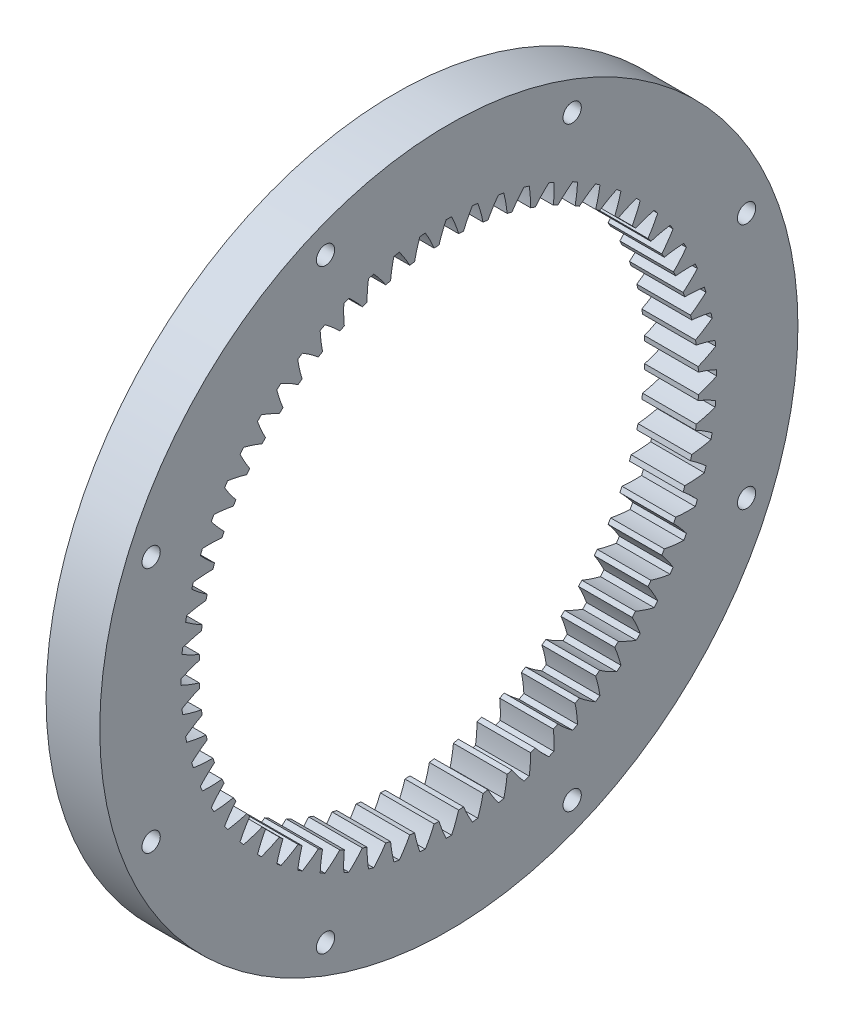
SolidWorks part; units mm, degrees
material "7075-O (SS)"
ref_plane "Plane1" through (0, 0, 0) normal (0, 0, 1) x (1, 0, 0)
ref_plane "Plane2" through (0, 0, 0) normal (0, 1, 0) x (1, 0, 0)
ref_plane "Plane3" through (0, 0, 0) normal (1, 0, 0) x (0, 0, -1)
sketch "HoldingSke" plane through (0, 0, 0) normal (0, 1, 0) x (1, 0, 0)
  line L0 (0, 0) -> (0.2922, -0.5992)
  line L1 (-15, 0) -> (100, 0) construction
  line L2 (0, 0) -> (-2.1039, 2.3779)
  line L3 (0, 0) -> (-11.863, 4.5341)
  line L4 (0, 0) -> (3.7858, 7.762)
  line L5 (0, 0) -> (-23.7986, -8.8762)
  line L6 (0, 0) -> (-10.5278, -7.1032)
  line L7 (-2.1039, 2.3779) -> (3.3635, 27.1825)
  line L8 (-76.2, 3.8779) -> (-54.61, 3.8779)
  line L9 (-71.009, 38.7566) -> (-53.1078, 45.2721)
  line L10 (-76.2, 71.12) -> (104.1128, 71.12)
  line L11 (0, 0) -> (-10, 0)
  line L12 (-76.2, 101.6) -> (-76.147, 101.6)
  line L13 (24.9733, 27.94) -> (52.9518, 28.4284)
  line L14 (24.9733, 27.94) -> (24.9743, 27.94)
  line L15 (24.9733, 27.94) -> (100.4006, 29.5858)
  circle A0 centre (0, 0) radius 55
  circle A1 centre (0, 0) radius 12.7
  circle A2 centre (0, 0) radius 12.7
  dimension "MHD" = 25.4
  dimension "Hub_dia" = 25.4
  dimension "Diameter" = 110
  dimension "Num_teeth" = 64
  dimension "Pitch" = 0.6667
  dimension "Overall_len" = 25.4
  dimension "Show_teeth" = 64
  dimension "Thickness" = 12.7
  dimension "OAL" = 25.4001
  dimension "T_dim" = 21.59
  dimension "Ap" = 20
  dimension "H" = 19.05
  dimension "Pitch_radius" = 180.3128
  dimension "Width" = 10
  dimension "Backlash" = 0.053
  dimension "Addendum_fac" = 1
  dimension "Dedendum_fac" = 1.25
  dimension "Clearance_fac" = 0.25
  dimension "Dedendum_add" = 0.001
  dimension "Module" = 1.5
sketch "BasProSke" plane through (0, 0, 0) normal (0, 1, 0) x (1, 0, 0)
  line L0 (-10, 0) -> (60, 0) construction
  line L1 (0, 46.5) -> (0, 55)
  line L2 (0, 46.5) -> (10, 46.5)
  line L3 (10, 46.5) -> (10, 55)
  line L4 (10, 55) -> (0, 55)
  dimension "Diameter" = 110
  dimension "Thickness" = 10
  dimension "Inside_diameter" = 93
revolve "Base-Revolve" add sketch "BasProSke" angle 360 about L0
sketch "TooCutSke" plane through (0, 0, 0) normal (1, 0, 0) x (0, 0, -1)
  line L3 (1.3105, 47.9821) -> (1.3105, 53.6633) construction
  line L4 (0, 0) -> (0, 59.563) construction
  line L5 (0, 0) -> (-3.3527, 68.2452) construction
  line L6 (-21.1794, 39.6032) -> (35.8053, 42.4027) construction
  circle A0 centre (0, 0) radius 48 construction
  circle A1 centre (0, 0) radius 49.876 construction
  circle A2 centre (0, 0) radius 40.5947 construction
  circle A3 centre (0, 0) radius 46.4746 construction
  arc A4 (1.8266, 46.4387) -> (0.5122, 49.8734) centre (-21.1794, 39.6032) ccw
  arc A5 (1.8266, 46.4387) -> (-1.8266, 46.4387) centre (0, 0) ccw
  arc A6 (0.5122, 49.8734) -> (-0.5122, 49.8734) centre (0, 0) ccw
  arc A7 (-0.5122, 49.8734) -> (-1.8266, 46.4387) centre (21.1794, 39.6032) ccw
  dimension "Pitch_dia" = 96
  dimension "Base_dia" = 81.1894
  dimension "Root_dia" = 99.752
  dimension "Overcut_dia" = 92.9492
  dimension "Flank_rad" = 24
  dimension "Half_ang" = 2.813
  dimension "Half_CT" = 1.3105
extrude "ToothCut" cut sketch "TooCutSke" along normal through all
fillet "Breaks" [suppressed] radius 0.15
fillet "RootFillets" [suppressed] radius 0.376
pattern_circular "TeethCuts" count 64 over 360 about axis through (0, 0, 0) along (1, 0, 0) of "RootFillets", "Breaks", "ToothCut"
sketch "Croquis1" plane through (10, 0, 0) normal (1, 0, 0) x (0, 0, -1)
  circle A0 centre (0, 0) radius 65
  circle A1 centre (0, 0) radius 55 construction
  circle A2 centre (0, 0) radius 55
  dimension "DiametroExterior" = 130
extrude "Saliente-Extruir1" add sketch "Croquis1" against normal up to surface (10 mm away) up to face at (0, 0, 55)
hole_wizard "Taladro de margen para M31" positions "Croquis2" profile "Croquis3" hole size "M3" standard "Ansi Metric"
sketch "Croquis2" plane through (10, 0, 0) normal (1, 0, 0) x (0, 0, -1)
  line L0 (0, 0) -> (22.961, 55.4328) construction
  line L3 (0, 0) -> (-22.961, -55.4328) construction
  point P0 (22.961, 55.4328)
  point P13 (55.4328, 22.961)
  point P14 (55.4328, -22.961)
  point P15 (22.961, -55.4328)
  point P16 (-22.961, -55.4328)
  point P17 (-55.4328, -22.961)
  point P18 (-55.4328, 22.961)
  point P19 (-22.961, 55.4328)
  dimension "RadioTaladro" = 60
  dimension "D2" = 22.5
  dimension "D3" = 8
sketch "Croquis3" plane through (10, 55.4328, -22.961) normal (0, 1, 0) x (0, 0, -1)
  line L0 (0, 0) -> (0, 11.0215)
  line L1 (0, 11.0215) -> (1.7, 10)
  line L2 (1.7, 10) -> (1.7, 0)
  line L5 (1.7, 0) -> (0, 0)
  line L10 (0, 11.0215) -> (-1.7, 10) construction
  line L11 (0, -6.35) -> (0, 107.95) construction
  dimension "Diámetro de taladro" = 3.4
  dimension "Profundidad de taladro" = 10
  dimension "Ángulo de perforador" = 118
equation "' \"Module@HoldingSke\" = 6.35"
equation "' \"Num_teeth@HoldingSke\" = 24"
equation "' \"Ap@HoldingSke\" =  14.5"
equation "' \"Ap@HoldingSke\" = 14.5"
equation "' \"Width@HoldingSke\" = 12"
equation "' \"Diameter@HoldingSke\" = 8 * 25.4"
equation "' \"Show_teeth@HoldingSke\" = 100"
equation "' \"Backlash@HoldingSke\" = 0.009 * 25.4"
equation "' \"Addendum_fac@HoldingSke\" = 1.0"
equation "' \"Dedendum_fac@HoldingSke\" = 1.25"
equation "' \"Dedendum_add@HoldingSke\" = 0.00005 * 25.4"
equation "' \"Clearance_fac@HoldingSke\" = 0.25"
equation "\"Pitch@HoldingSke\" = 1 / \"Module@HoldingSke\" "
equation "\"Overcut_dia@TooCutSke\" = (\"Num_teeth@HoldingSke\" - 2 * \"Addendum_fac@HoldingSke\") / \"Pitch@HoldingSke\" - 0.002 * 25.4"
equation "\"Pitch_dia@TooCutSke\" = \"Num_teeth@HoldingSke\" / \"Pitch@HoldingSke\""
equation "\"Base_dia@TooCutSke\" = \"Num_teeth@HoldingSke\" / \"Pitch@HoldingSke\" * cos((\"Ap@HoldingSke\"  * 3.14159265 / 180)) * 0.90"
equation "\"Root_dia@TooCutSke\" = \"Num_teeth@HoldingSke\"  / \"Pitch@HoldingSke\" + 2 *  \"Dedendum_fac@HoldingSke\"/ \"Pitch@HoldingSke\" + \"Dedendum_add@HoldingSke\" * 2"
equation "\"Half_ang@TooCutSke\" = 180 / \"Num_teeth@HoldingSke\""
equation "\"Half_CT@TooCutSke\" = \"Num_teeth@HoldingSke\" / \"Pitch@HoldingSke\" * sin((3.14159265 / 2 / \"Num_teeth@HoldingSke\")) / 2 + 10 * \"Backlash@HoldingSke\" / 4"
equation "\"Flank_rad@TooCutSke\" = \"Num_teeth@HoldingSke\" / \"Pitch@HoldingSke\" / 4"
equation "\"Radius@RootFillets\"= \"Clearance_fac@HoldingSke\" / \"Pitch@HoldingSke\" + \"Dedendum_add@HoldingSke\""
equation "\"Break_rad@Breaks\" = 0.02 / \"Pitch@HoldingSke\" * 5"
equation "\"Num_teeth@TeethCuts\" = int( \"Show_teeth@HoldingSke\" ) + 1"
equation "\"Num_teeth@TeethCuts\" = ((sgn( \"Num_teeth@TeethCuts\" - \"Num_teeth@HoldingSke\" )-1)*( \"Num_teeth@TeethCuts\" - \"Num_teeth@HoldingSke\" ))/-2+ \"Num_teeth@HoldingSke\""
equation "\"Num_teeth@TeethCuts\" = ((sgn( \"Num_teeth@TeethCuts\" - 2.0)+1)*( \"Num_teeth@TeethCuts\" - 2.0))/2 +2.0"
equation "\"Angle@TeethCuts\" = 360.0 / \"Num_teeth@HoldingSke\""
equation "\"Diameter@BasProSke\" = \"Num_teeth@HoldingSke\"  / \"Pitch@HoldingSke\" + 2 *  \"Dedendum_fac@HoldingSke\"/ \"Pitch@HoldingSke\" + \"Dedendum_add@HoldingSke\" * 2 + 0.002 * 25.4"
equation "\"Diameter@BasProSke\" = ((sgn( \"Diameter@BasProSke\"  - \"Diameter@HoldingSke\" )+1)*( \"Diameter@BasProSke\"  - \"Diameter@HoldingSke\" ))/2 + \"Diameter@HoldingSke\""
equation "\"Inside_diameter@BasProSke\" =  (\"Num_teeth@HoldingSke\" - 2 * \"Addendum_fac@HoldingSke\") / \"Pitch@HoldingSke\" "
equation "\"Thickness@BasProSke\"  = \"Width@HoldingSke\""
